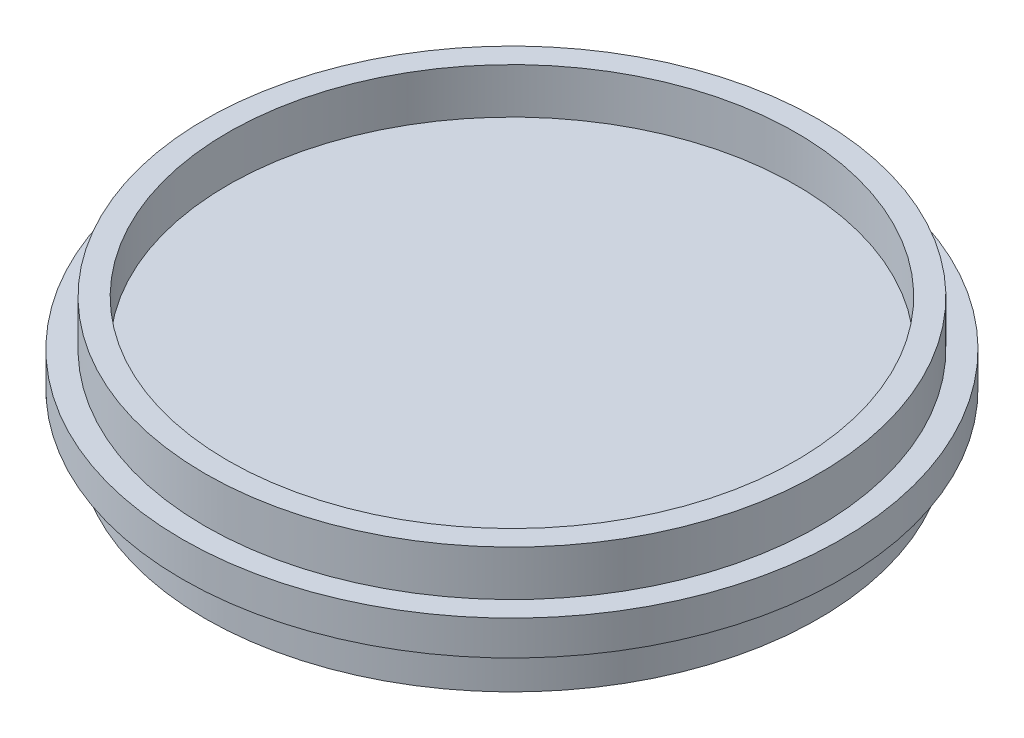
SolidWorks part; units mm, degrees
material "6061-T6 (SS)"
ref_plane "Front Plane" through (0, 0, 0) normal (0, 0, 1) x (1, 0, 0)
ref_plane "Top Plane" through (0, 0, 0) normal (0, 1, 0) x (1, 0, 0)
ref_plane "Right Plane" through (0, 0, 0) normal (1, 0, 0) x (0, 0, -1)
sketch "Sketch1" plane through (0, 0, 0) normal (0, 1, 0) x (1, 0, 0)
  circle A0 centre (0, 0) radius 92.075
  dimension "D1" = 184.15
extrude "Boss-Extrude1" add sketch "Sketch1" along normal mid plane 9.652
sketch "Sketch2" plane through (0, 0, 0) normal (0, 0, 1) x (1, 0, 0)
  line L0 (0, -18.3275) -> (0, 20.8308) construction
  line L1 (0, -4.826) -> (-19.297, -4.826)
  line L2 (-92.075, -4.826) -> (92.075, -4.826) construction
  line L3 (0, -4.826) -> (0, -1.4952)
  line L4 (-0.3818, -1.4952) -> (0, -1.4952)
  arc A0 (-19.297, -4.826) -> (-0.3818, -1.4952) centre (-0.4072, -56.7254) cw
  dimension "D6" = 55.2302
  dimension "D1" = 19.297
  dimension "D2" = 3.3308
  dimension "D3" = 0.3818
revolve "Cut-Revolve1" [suppressed] cut sketch "Sketch2" angle 360 about L0
sketch "Sketch4" plane through (0, 4.826, 0) normal (0, 1, 0) x (1, 0, 0)
  circle A0 centre (0, 0) radius 85.725
  circle A1 centre (0, 0) radius 79.375
  dimension "D1" = 171.45
  dimension "D2" = 158.75
extrude "Boss-Extrude2" add sketch "Sketch4" along normal blind 12.7
ref_plane "Plane1" through (0, 0, -85.725) normal (0, 0, -1) x (-1, 0, 0)
sketch "Sketch5" plane through (0, 0, -85.725) normal (0, 0, -1) x (-1, 0, 0)
  line L0 (0, 55) -> (0, -55) construction
  line L1 (79.375, 17.526) -> (-79.375, 17.526) construction
  circle A0 centre (0, 11.176) radius 1.4351
  dimension "D1" = 2.8702
  dimension "D2" = 6.35
extrude "Cut-Extrude2" [suppressed] cut sketch "Sketch5" against normal blind 12.7
pattern_circular "CirPattern1" [suppressed] count 12 over 360
mirror "Mirror2" about plane through (0, 0, 0) normal (0, 1, 0) of "Boss-Extrude2"
sketch "Sketch6" plane through (0, 4.826, 0) normal (0, 1, 0) x (1, 0, 0)
  line L0 (-63.5, 0) -> (-69.85, 0)
  line L1 (0, -69.85) -> (0, -63.5)
  line L2 (0, -55) -> (0, 55) construction
  arc A0 (-69.85, 0) -> (0, -69.85) centre (0, 0) ccw
  arc A1 (-63.5, 0) -> (0, -63.5) centre (0, 0) ccw
  dimension "D1" = 69.85
  dimension "D2" = 63.5
  dimension "D3" = 90
extrude "Cut-Extrude3" [suppressed] cut sketch "Sketch6" against normal up to surface (9.652 mm away)
